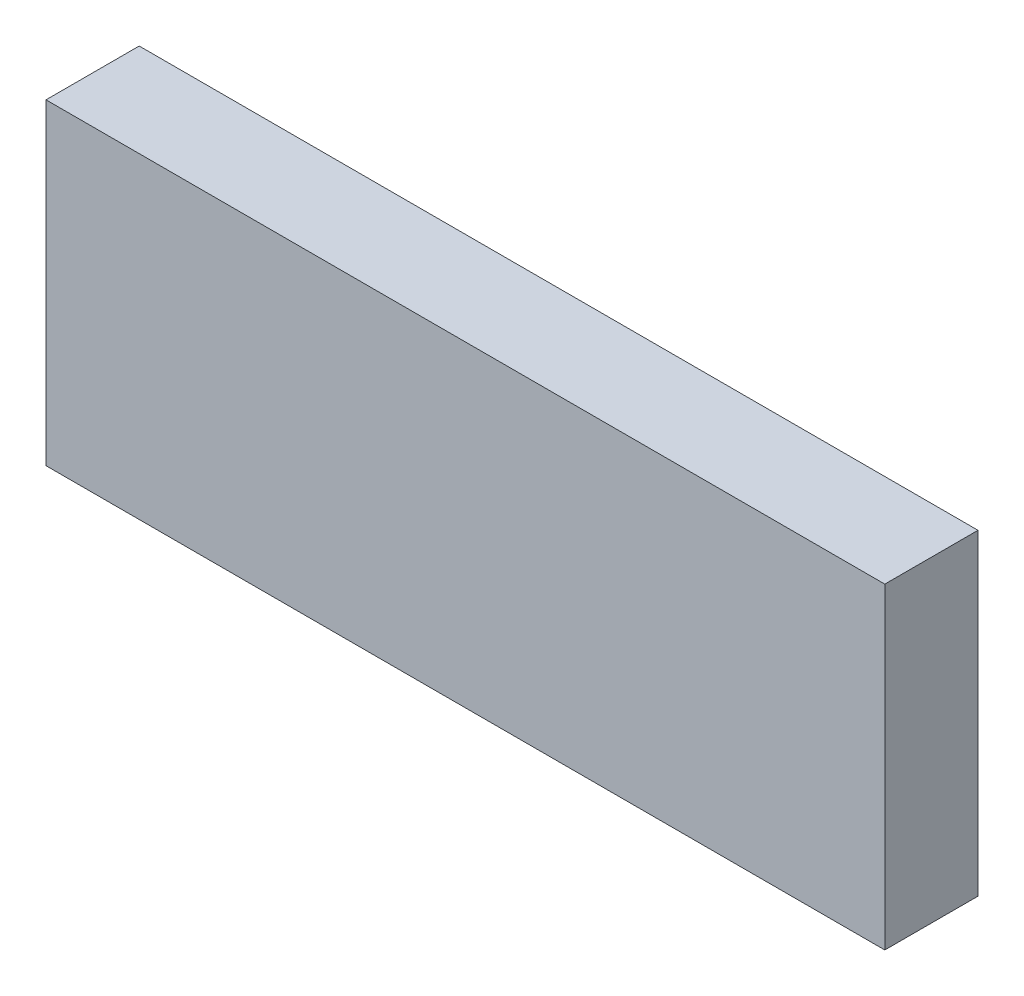
SolidWorks part; units mm, degrees
material "Alumina"
ref_plane "Front Plane" through (0, 0, 0) normal (0, 0, 1) x (1, 0, 0)
ref_plane "Top Plane" through (0, 0, 0) normal (0, 1, 0) x (1, 0, 0)
ref_plane "Right Plane" through (0, 0, 0) normal (1, 0, 0) x (0, 0, -1)
sketch "Sketch2" plane through (0, 0, 0) normal (0, 0, 1) x (1, 0, 0)
  line L1 (0, 0) -> (4500, 0)
  line L2 (0, 0) -> (0, 1700)
  line L3 (0, 1700) -> (4500, 1700)
  line L4 (4500, 0) -> (4500, 1700)
  dimension "D1" = 1700
  dimension "D2" = 4500
extrude "Boss-Extrude1" add sketch "Sketch2" along normal blind 500
